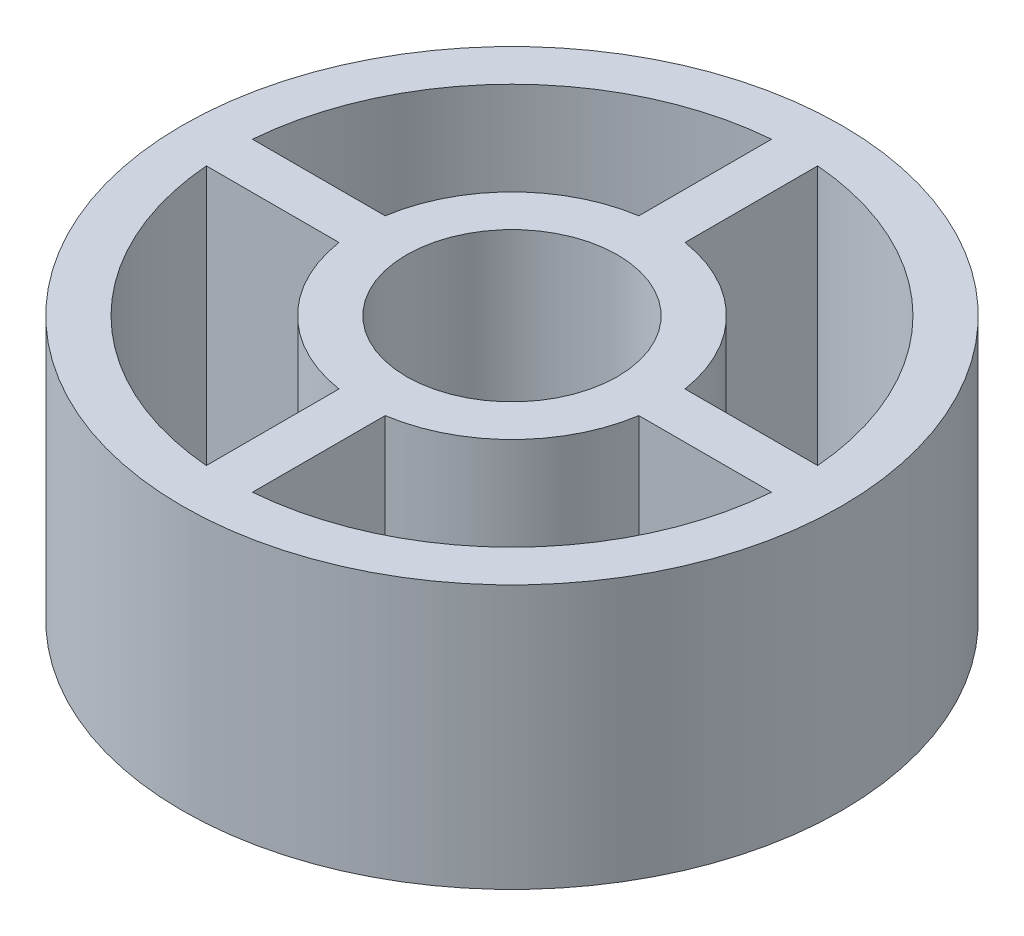
SolidWorks part; units mm, degrees
ref_plane "前视基准面" through (0, 0, 0) normal (0, 0, 1) x (1, 0, 0)
ref_plane "上视基准面" through (0, 0, 0) normal (0, 1, 0) x (1, 0, 0)
ref_plane "右视基准面" through (0, 0, 0) normal (1, 0, 0) x (0, 0, -1)
sketch "草图1" plane through (0, 0, 0) normal (0, 1, 0) x (1, 0, 0)
  line L0 (2.2732, 0.35) -> (4.2857, 0.35)
  line L1 (4.2857, -0.35) -> (2.2732, -0.35)
  line L2 (0, 0) -> (5.7293, 0) construction
  line L3 (-0.35, -4.2857) -> (-0.35, -2.2732)
  line L4 (0.35, -2.2732) -> (0.35, -4.2857)
  line L5 (-4.2857, 0.35) -> (-2.2732, 0.35)
  line L6 (-2.2732, -0.35) -> (-4.2857, -0.35)
  line L7 (0.35, 4.2857) -> (0.35, 2.2732)
  line L8 (-0.35, 2.2732) -> (-0.35, 4.2857)
  circle A0 centre (0, 0) radius 1.6
  arc A1 (-0.35, 2.2732) -> (-2.2732, 0.35) centre (0, 0) ccw
  circle A2 centre (0, 0) radius 5
  arc A3 (4.2857, 0.35) -> (0.35, 4.2857) centre (0, 0) ccw
  arc A4 (2.2732, 0.35) -> (0.35, 2.2732) centre (0, 0) ccw
  arc A5 (-0.35, 4.2857) -> (-4.2857, 0.35) centre (0, 0) ccw
  arc A6 (-4.2857, -0.35) -> (-0.35, -4.2857) centre (0, 0) ccw
  arc A7 (-2.2732, -0.35) -> (-0.35, -2.2732) centre (0, 0) ccw
  arc A8 (0.35, -2.2732) -> (2.2732, -0.35) centre (0, 0) ccw
  arc A9 (0.35, -4.2857) -> (4.2857, -0.35) centre (0, 0) ccw
  point P26 (0, 0)
  dimension "D1" = 3.2
  dimension "D2" = 0.7
  dimension "D3" = 10
  dimension "D4" = 0.7
  dimension "D5" = 0.7
  dimension "D6" = 4
extrude "凸台-拉伸1" add sketch "草图1" along normal blind 4
